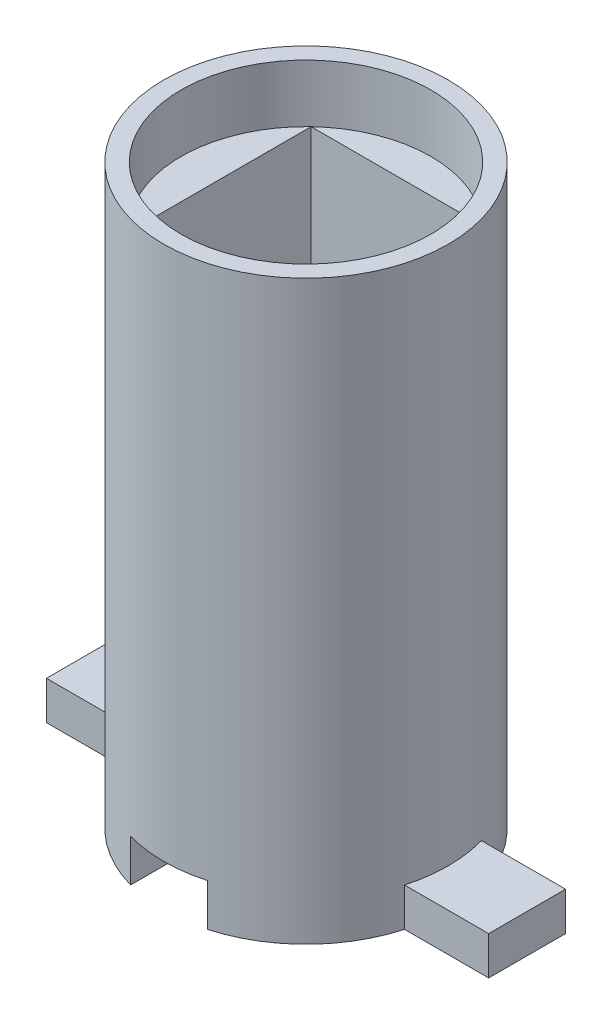
SolidWorks part; units mm, degrees
ref_plane "Front Plane" through (0, 0, 0) normal (0, 0, 1) x (1, 0, 0)
ref_plane "Top Plane" through (0, 0, 0) normal (0, 1, 0) x (1, 0, 0)
ref_plane "Right Plane" through (0, 0, 0) normal (1, 0, 0) x (0, 0, -1)
sketch "Sketch1" plane through (0, 0, 0) normal (0, 1, 0) x (1, 0, 0)
  circle A0 centre (0, 0) radius 37
  dimension "D1" = 74
extrude "Boss-Extrude1" add sketch "Sketch1" along normal blind 150
sketch "Sketch2" plane through (0, 150, 0) normal (0, 1, 0) x (1, 0, 0)
  line L1 (-11.5, 11.5) -> (11.5, 11.5)
  line L2 (-11.5, 11.5) -> (-11.5, -11.5)
  line L3 (-11.5, -11.5) -> (11.5, -11.5)
  line L4 (11.5, 11.5) -> (11.5, -11.5)
  line L5 (-11.5, 11.5) -> (11.5, -11.5) construction
  line L6 (-11.5, -11.5) -> (11.5, 11.5) construction
  point P0 (0, 0)
  dimension "D1" = 23
  dimension "D2" = 23
extrude "Cut-Extrude1" cut sketch "Sketch2" against normal blind 150
sketch "Sketch3" plane through (0, 0, 0) normal (0, -1, 0) x (1, 0, 0)
  line L1 (-21.5, 21.5) -> (21.5, 21.5)
  line L2 (-21.5, 21.5) -> (-21.5, -21.5)
  line L3 (-21.5, -21.5) -> (21.5, -21.5)
  line L4 (21.5, 21.5) -> (21.5, -21.5)
  line L5 (-21.5, 21.5) -> (21.5, -21.5) construction
  line L6 (-21.5, -21.5) -> (21.5, 21.5) construction
  point P0 (0, 0)
  dimension "D1" = 43
  dimension "D2" = 43
extrude "Cut-Extrude2" cut sketch "Sketch3" against normal blind 36
chamfer "Chamfer1" distance 5 angle 45 4 edges at (21.5, 18, 21.5) (-21.5, 18, 21.5) (-21.5, 18, -21.5) (21.5, 18, -21.5)
sketch "Sketch5" plane through (0, 150, 0) normal (0, 1, 0) x (1, 0, 0)
  circle A0 centre (0, 0) radius 32.5
  dimension "D1" = 65
extrude "Cut-Extrude3" cut sketch "Sketch5" against normal blind 15
sketch "Sketch11" plane through (0, 135, 0) normal (0, 1, 0) x (1, 0, 0)
  line L1 (-22.3036, 23.6389) -> (22.3036, 23.6389)
  line L2 (-22.3036, 23.6389) -> (-22.3036, -23.6389)
  line L3 (-22.3036, -23.6389) -> (22.3036, -23.6389)
  line L4 (22.3036, 23.6389) -> (22.3036, -23.6389)
  line L5 (-22.3036, 23.6389) -> (22.3036, -23.6389) construction
  line L6 (-22.3036, -23.6389) -> (22.3036, 23.6389) construction
  circle A0 centre (0, 0) radius 32.5 construction
  point P0 (0, 0)
extrude "Cut-Extrude7" cut sketch "Sketch11" against normal blind 104
sketch "Sketch12" plane through (0, 0, 0) normal (0, -1, 0) x (1, 0, 0)
  line L0 (21.5, -16.5) -> (21.5, 16.5) construction
  line L1 (-47.5, 10) -> (-21.5, 10)
  line L2 (-47.5, 10) -> (-47.5, -10)
  line L3 (-47.5, -10) -> (-21.5, -10)
  line L4 (47.5, 10) -> (47.5, -10)
  line L5 (-47.5, 10) -> (-21.5, 4.5263) construction
  line L6 (-47.5, -10) -> (-21.5, -4.5263) construction
  line L8 (-21.5, 10) -> (-21.5, -10)
  line L10 (21.5, 10) -> (21.5, -10)
  line L13 (21.5, 10) -> (47.5, 10)
  line L14 (21.5, -4.5263) -> (47.5, -10) construction
  line L15 (21.5, 4.5263) -> (47.5, 10) construction
  line L16 (21.5, -10) -> (47.5, -10)
  point P0 (0, 0)
  point P6 (0, 0)
  dimension "D1" = 95
  dimension "D2" = 20
extrude "Boss-Extrude2" add sketch "Sketch12" against normal blind 10
sketch "Sketch13" plane through (0, 0, 0) normal (0, -1, 0) x (1, 0, 0)
  line L0 (0, 0) -> (0, 37) construction
  line L1 (16.5, 21.5) -> (-16.5, 21.5) construction
  line L2 (-10, 52.5) -> (10, 52.5)
  line L3 (-10, 52.5) -> (-10, 21.5)
  line L4 (-10, 21.5) -> (10, 21.5)
  line L5 (10, 52.5) -> (10, 21.5)
  line L6 (-10, 52.5) -> (10, 21.5) construction
  line L7 (-10, 21.5) -> (10, 52.5) construction
  arc A0 (35.623, 10) -> (-35.623, 10) centre (0, 0) ccw construction
  dimension "D1" = 20
extrude "Cut-Extrude8" cut sketch "Sketch13" against normal blind 11
sketch "Sketch14" plane through (47.5, 0, 0) normal (1, 0, 0) x (0, 0, -1)
  line L1 (-10, 10) -> (10, 10)
  line L2 (-10, 10) -> (-10, 0)
  line L3 (-10, 0) -> (10, 0)
  line L4 (10, 10) -> (10, 0)
extrude "Boss-Extrude3" add sketch "Sketch14" along normal blind 10
sketch "Sketch15" plane through (-47.5, 0, 0) normal (-1, 0, 0) x (0, 0, 1)
  line L1 (-10, 10) -> (10, 10)
  line L2 (-10, 10) -> (-10, 0)
  line L3 (-10, 0) -> (10, 0)
  line L4 (10, 10) -> (10, 0)
extrude "Boss-Extrude4" add sketch "Sketch15" along normal blind 10
